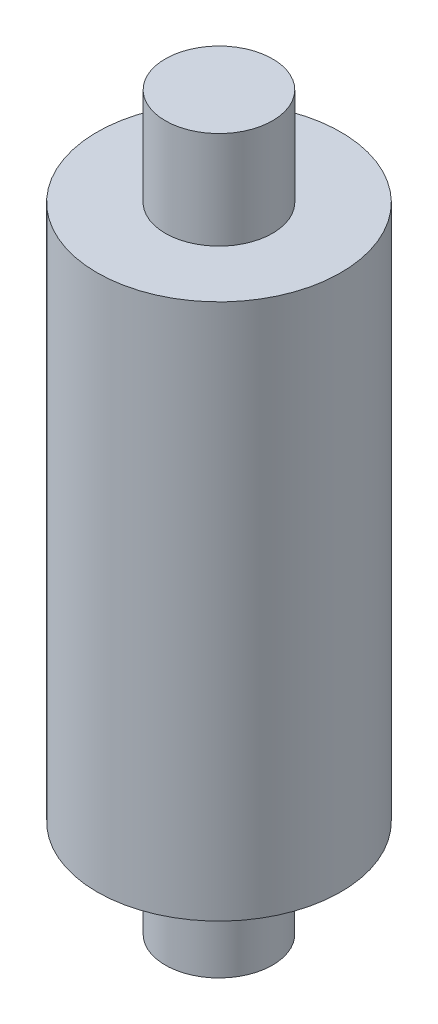
SolidWorks part; units mm, degrees
ref_plane "Спереди" through (0, 0, 0) normal (0, 0, 1) x (1, 0, 0)
ref_plane "Сверху" through (0, 0, 0) normal (0, 1, 0) x (1, 0, 0)
ref_plane "Справа" through (0, 0, 0) normal (1, 0, 0) x (0, 0, -1)
sketch "Эскиз1" plane through (0, 0, 0) normal (0, 1, 0) x (1, 0, 0)
  circle A0 centre (0, 0) radius 2.5
  dimension "D1" = 5
extrude "Бобышка-Вытянуть1" add sketch "Эскиз1" along normal blind 11
sketch "Эскиз2" plane through (0, 11, 0) normal (0, 1, 0) x (1, 0, 0)
  circle A0 centre (0, 0) radius 1.1
  dimension "D1" = 2.2
extrude "Бобышка-Вытянуть2" add sketch "Эскиз2" along normal blind 2
sketch "Эскиз4" plane through (0, 0, 0) normal (0, -1, 0) x (1, 0, 0)
  circle A0 centre (0, 0) radius 1.1
  circle A1 centre (0, 0) radius 1.1 construction
extrude "Бобышка-Вытянуть3" add sketch "Эскиз4" along normal blind 2
